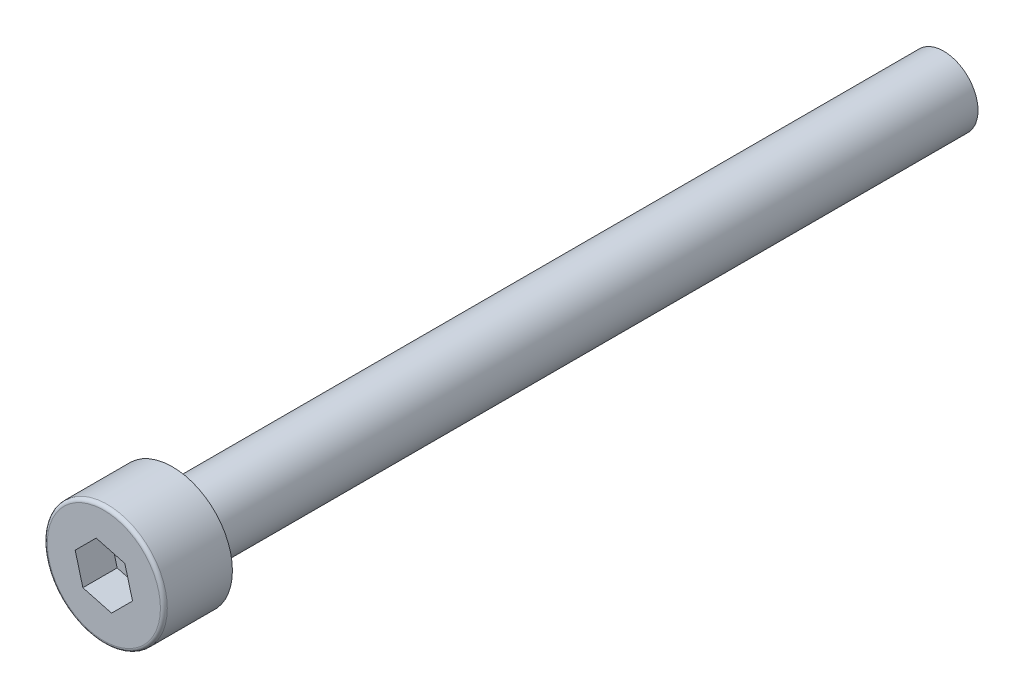
SolidWorks part; units mm, degrees
ref_plane "前视基准面" through (0, 0, 0) normal (0, 0, 1) x (1, 0, 0)
ref_plane "上视基准面" through (0, 0, 0) normal (0, 1, 0) x (1, 0, 0)
ref_plane "右视基准面" through (0, 0, 0) normal (1, 0, 0) x (0, 0, -1)
sketch "草图1" plane through (0, 0, 0) normal (0, 0, 1) x (1, 0, 0)
  circle A0 centre (0, 0) radius 3.5
  dimension "D1" = 7
extrude "凸台-拉伸1" add sketch "草图1" along normal blind 4
sketch "草图2" plane through (0, 0, 4) normal (0, 0, 1) x (1, 0, 0)
  line L1 (-1.2247, -1.2247) -> (0.4483, -1.673)
  line L2 (0.4483, -1.673) -> (1.673, -0.4483)
  line L3 (1.673, -0.4483) -> (1.2247, 1.2247)
  line L4 (1.2247, 1.2247) -> (-0.4483, 1.673)
  line L5 (-0.4483, 1.673) -> (-1.673, 0.4483)
  line L6 (-1.673, 0.4483) -> (-1.2247, -1.2247)
  circle A0 centre (0, 0) radius 1.5 construction
  dimension "D1" = 3
extrude "切除-拉伸1" cut sketch "草图2" against normal blind 2
sketch "草图3" plane through (0, 0, 0) normal (0, 0, -1) x (-1, 0, 0)
  circle A0 centre (0, 0) radius 2
  dimension "D1" = 4
extrude "凸台-拉伸2" add sketch "草图3" along normal blind 45
fillet "圆角1" radius 0.2 1 edges at (3.5, 0, 4)
